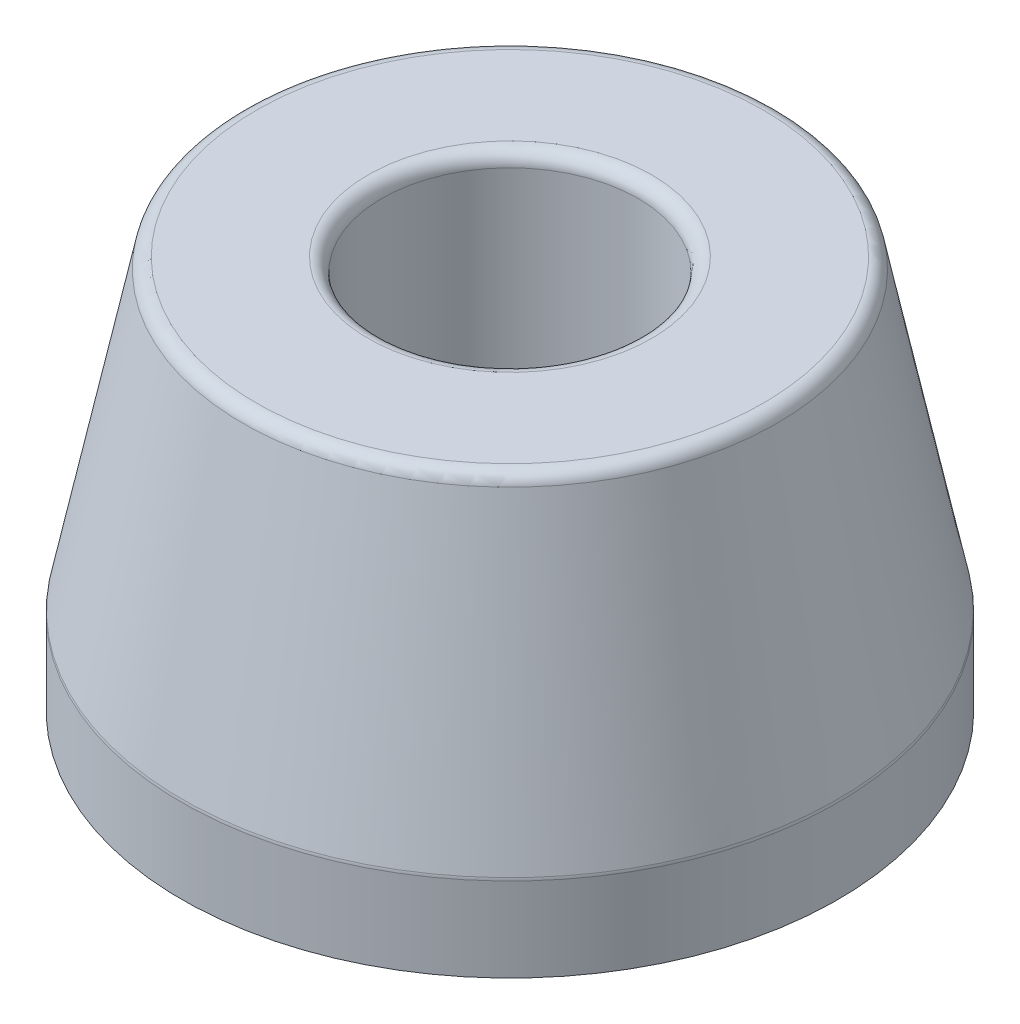
SolidWorks part; units mm, degrees
material "POLYURETHANE (11671)"
ref_plane "Front" through (0, 0, 0) normal (0, 0, 1) x (1, 0, 0)
ref_plane "Top" through (0, 0, 0) normal (0, 1, 0) x (1, 0, 0)
ref_plane "Right" through (0, 0, 0) normal (1, 0, 0) x (0, 0, -1)
sketch "Sketch1" plane through (0, 0, 0) normal (0, 0, 1) x (1, 0, 0)
  line L0 (4.7625, 0) -> (4.7625, 14.097)
  line L1 (5.2705, 14.605) -> (9.4283, 14.605)
  line L2 (9.9259, 14.1993) -> (12.1816, 3.2256)
  line L3 (12.192, 3.1233) -> (12.192, 0)
  line L4 (12.192, 0) -> (4.7625, 0)
  line L5 (0, 0) -> (0, 14.605) construction
  arc A0 (12.1816, 3.2256) -> (12.192, 3.1233) centre (11.684, 3.1233) cw
  arc A1 (4.7625, 14.097) -> (5.2705, 14.605) centre (5.2705, 14.097) cw
  arc A2 (9.4283, 14.605) -> (9.9259, 14.1993) centre (9.4283, 14.097) cw
  point P8 (12.192, 3.175)
  point P11 (4.7625, 14.605)
  point P14 (9.8425, 14.605)
  dimension "D6" = 0.508
  dimension "D1" = 14.605
  dimension "D2" = 4.7625
  dimension "D3" = 5.08
  dimension "D4" = 3.175
  dimension "D5" = 24.384
revolve "Revolve1" add sketch "Sketch1" angle 360 about L5
